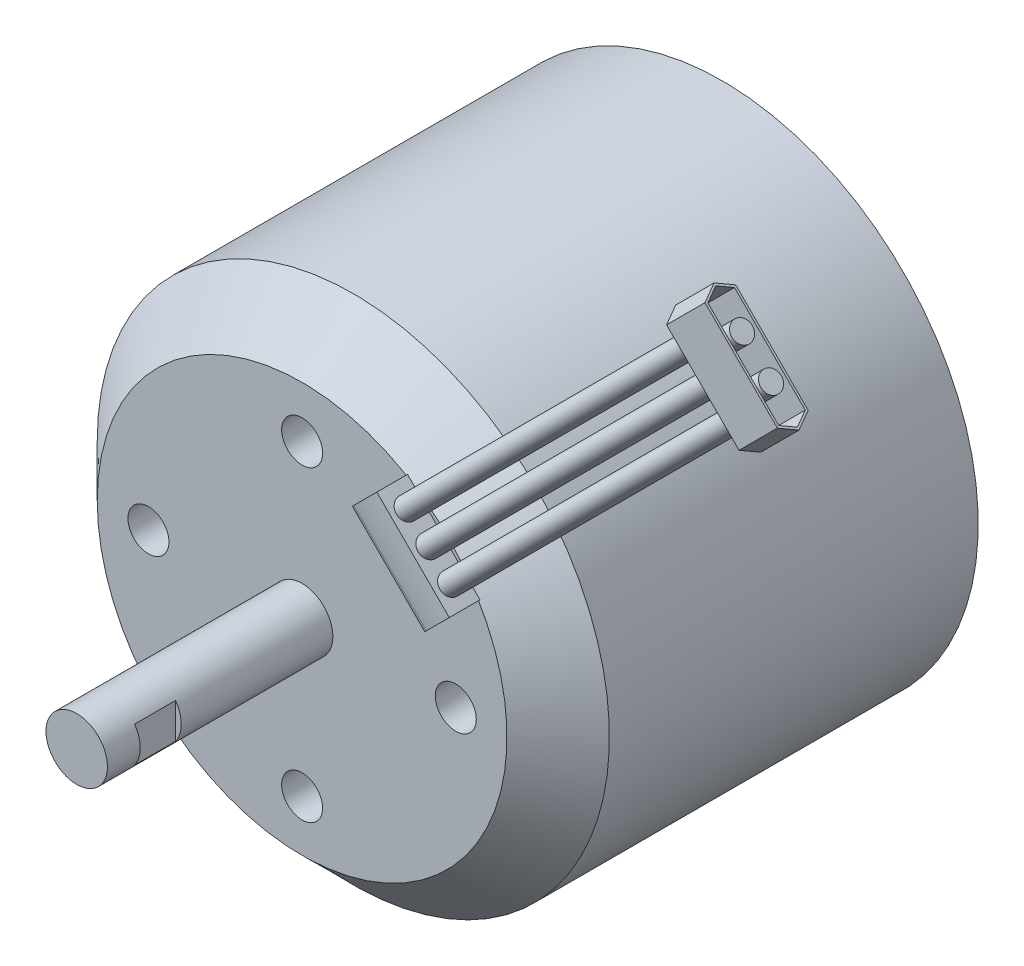
SolidWorks part; units mm, degrees
material "复合材料"
ref_plane "前视基准面" through (0, 0, 0) normal (0, 0, 1) x (1, 0, 0)
ref_plane "上视基准面" through (0, 0, 0) normal (0, 1, 0) x (1, 0, 0)
ref_plane "右视基准面" through (0, 0, 0) normal (1, 0, 0) x (0, 0, -1)
sketch "草图1" plane through (0, 0, 0) normal (1, 0, 0) x (0, 0, -1)
  line L0 (0, 0) -> (-91.143, 0) construction
  line L1 (0, 0) -> (0, 95.1998) construction
  line L2 (-2, 25) -> (-38, 25)
  line L4 (-43, 20) -> (-43, 3)
  line L5 (-43, 3) -> (-65, 3)
  line L6 (-65, 3) -> (-65, 0)
  line L7 (-65, 0) -> (0, 0)
  line L9 (-2, 25) -> (-2, 3)
  line L10 (-2, 3) -> (0, 3)
  line L11 (0, 3) -> (0, 0)
  line L12 (-38, 25) -> (-43, 20)
  dimension "D1" = 65
  dimension "D2" = 22
  dimension "D3" = 6
  dimension "D4" = 41
  dimension "D5" = 6
  dimension "D6" = 50
  dimension "D7" = 5
  dimension "D8" = 135
revolve "旋转1" add sketch "草图1" angle 360 about L0
sketch "草图2" plane through (0, 0, 43) normal (0, 0, 1) x (1, 0, 0)
  circle A0 centre (0, 0) radius 15 construction
  dimension "D1" = 30
sketch "草图3" plane through (0, 0, 2) normal (0, 0, -1) x (-1, 0, 0)
  circle A0 centre (0, 0) radius 10 construction
  dimension "D1" = 20
hole_wizard "M4 螺纹孔1" positions "草图4" profile "草图5" tap size "M4" standard "GB"
sketch "草图4" plane through (0, 0, 43) normal (0, 0, 1) x (1, 0, 0)
  circle A0 centre (0, 0) radius 15 construction
  point P0 (0, 15)
  point P4 (15, 0)
  point P6 (0, -15)
  point P8 (-15, 0)
sketch "草图5" plane through (0, 15, 43) normal (1, 0, 0) x (0, -1, 0)
  line L0 (0, 0) -> (0, 7.3017)
  line L1 (0, 7.3017) -> (2, 6.1)
  line L2 (2, 6.1) -> (2, 0)
  line L5 (2, 0) -> (0, 0)
  line L10 (0, 7.3017) -> (-2, 6.1) construction
  line L11 (0, -6.35) -> (0, 107.95) construction
  dimension "螺纹孔钻头直径" = 4
  dimension "螺纹孔钻头深度" = 6.1
  dimension "导头角度" = 118
cosmetic thread "孔螺蚊线1" parameters "D1"=4, "D2"=4
cosmetic thread "孔螺蚊线2" parameters "D1"=4, "D2"=4
cosmetic thread "孔螺蚊线3" parameters "D1"=4, "D2"=4
cosmetic thread "孔螺蚊线4" parameters "D1"=4, "D2"=4
hole_wizard "M3 螺纹孔1" positions "草图6" profile "草图7" tap size "M3" standard "GB"
sketch "草图6" plane through (0, 0, 2) normal (0, 0, -1) x (-1, 0, 0)
  circle A0 centre (0, 0) radius 10 construction
  point P0 (0, 10)
  point P4 (10, 0)
  point P6 (0, -10)
  point P8 (-10, 0)
sketch "草图7" plane through (0, 10, 2) normal (1, 0, 0) x (0, 1, 0)
  line L0 (0, 0) -> (0, 6.4013)
  line L1 (0, 6.4013) -> (1.5, 5.5)
  line L2 (1.5, 5.5) -> (1.5, 0)
  line L5 (1.5, 0) -> (0, 0)
  line L10 (0, 6.4013) -> (-1.5, 5.5) construction
  line L11 (0, -6.35) -> (0, 107.95) construction
  dimension "螺纹孔钻头直径" = 3
  dimension "螺纹孔钻头深度" = 5.5
  dimension "导头角度" = 118
cosmetic thread "孔螺蚊线5" parameters "D1"=4, "D2"=3
cosmetic thread "孔螺蚊线6" parameters "D1"=4, "D2"=3
cosmetic thread "孔螺蚊线7" parameters "D1"=4, "D2"=3
cosmetic thread "孔螺蚊线8" parameters "D1"=4, "D2"=3
sketch "草图8" plane through (0, 0, 43) normal (0, 0, 1) x (1, 0, 0)
  line L0 (0, 26.4035) -> (0, 0) construction
  line L5 (6.7175, 13.7886) -> (13.7886, 6.7175)
  line L6 (6.7175, 13.7886) -> (8.8388, 15.9099)
  line L7 (8.8388, 15.9099) -> (15.9099, 8.8388)
  line L8 (13.7886, 6.7175) -> (15.9099, 8.8388)
  line L9 (6.7175, 13.7886) -> (15.9099, 8.8388) construction
  line L10 (8.8388, 15.9099) -> (13.7886, 6.7175) construction
  line L11 (0, 0) -> (21.7327, 21.7327) construction
  point P0 (11.3137, 11.3137)
  dimension "D1" = 45
  dimension "D2" = 10
  dimension "D3" = 3
  dimension "D4" = 16
ref_plane "基准面1" through (0, 0, 0) normal (-0.7071, 0.7071, 0) x (0.7071, 0.7071, 0)
sketch "草图9" plane through (0, 0, 0) normal (-0.7071, 0.7071, 0) x (0.7071, 0.7071, 0)
  line L1 (16, -43) -> (16, -40.4916) construction
  line L2 (16, -41.4826) -> (16, -43) construction
  line L3 (21.0176, -45.5321) -> (30.1015, -45.5321) construction
  line L4 (17.316, -44.8794) -> (18, -43) construction
  line L5 (21.0176, -45.5321) -> (18, -43) construction
  line L6 (18.6701, -43) -> (0, -43) construction
  arc A0 (16, -43) -> (17.316, -44.8794) centre (18, -43) ccw
  arc A1 (17.316, -44.8794) -> (21.0176, -45.5321) centre (21.0176, -34.7091) ccw
  dimension "D1" = 2
  dimension "D2" = 70
  dimension "D3" = 70
sweep "扫描1" add profiles "草图8" path "草图9"
sketch "草图11" plane through (14.8617, 14.8617, 0) normal (0.7071, 0.7071, 0) x (0, 0, -1)
  line L0 (-47.0321, 0) -> (-44.0321, 0) construction
  line L1 (-47.0321, 5) -> (-47.0321, -5) construction
  line L2 (-44.0321, -5) -> (-44.0321, 5) construction
  line L3 (-45.5321, -5) -> (-45.5321, 5) construction
  line L4 (-47.0321, -5) -> (-44.0321, -5) construction
  line L5 (-44.0321, 5) -> (-47.0321, 5) construction
  circle A0 centre (-45.5321, 0) radius 1
  circle A1 centre (-45.5321, 3) radius 1
  circle A2 centre (-45.5321, -3) radius 1
  dimension "D1" = 6
  dimension "2" = 2
extrude "凸台-拉伸1" add sketch "草图11" along normal blind 40
sketch "草图12" plane through (43.146, 43.146, 0) normal (0.7071, 0.7071, 0) x (0, 0, -1)
  line L0 (-45.5321, 5) -> (-45.5321, -5) construction
  line L1 (-47.0321, -5) -> (-45.5321, -5.866)
  line L2 (-45.5321, -5.866) -> (-44.0321, -5)
  line L3 (-47.0321, 0) -> (-44.0321, 0) construction
  line L4 (-47.0321, -5) -> (-44.0321, -5)
  line L5 (-44.0321, -5) -> (-44.0321, 5)
  line L6 (-44.0321, 5) -> (-47.0321, 5)
  line L7 (-47.0321, 5) -> (-47.0321, -5)
  line L8 (-47.0321, -5) -> (-44.0321, -5) construction
  line L9 (-44.0321, -5) -> (-44.0321, 5)
  line L10 (-44.0321, 5) -> (-47.0321, 5) construction
  line L11 (-47.0321, 5) -> (-47.0321, -5)
  line L12 (-45.5321, 5.866) -> (-44.0321, 5)
  line L13 (-47.0321, 5) -> (-45.5321, 5.866)
  dimension "D2" = 120
  dimension "D1" = 0
extrude "凸台-拉伸2" add sketch "草图12" along normal blind 0.3
sketch "草图13" plane through (43.3581, 43.3581, 0) normal (0.7071, 0.7071, 0) x (0, 0, -1)
  line L0 (-46.8321, 4.8845) -> (-46.8321, -4.8845)
  line L1 (-46.8321, -4.8845) -> (-45.5321, -5.6351)
  line L2 (-45.5321, -5.6351) -> (-44.2321, -4.8845)
  line L3 (-44.2321, -4.8845) -> (-44.2321, 4.8845)
  line L4 (-44.2321, 4.8845) -> (-45.5321, 5.6351)
  line L5 (-45.5321, 5.6351) -> (-46.8321, 4.8845)
  line L6 (-47.0321, 5) -> (-47.0321, -5)
  line L7 (-47.0321, -5) -> (-45.5321, -5.866)
  line L8 (-45.5321, -5.866) -> (-44.0321, -5)
  line L9 (-44.0321, -5) -> (-44.0321, 5)
  line L10 (-44.0321, 5) -> (-45.5321, 5.866)
  line L11 (-45.5321, 5.866) -> (-47.0321, 5)
  line L12 (-47.0321, 5) -> (-47.0321, -5)
  line L13 (-47.0321, -5) -> (-45.5321, -5.866)
  line L14 (-45.5321, -5.866) -> (-44.0321, -5)
  line L15 (-44.0321, -5) -> (-44.0321, 5)
  line L16 (-44.0321, 5) -> (-45.5321, 5.866)
  line L17 (-45.5321, 5.866) -> (-47.0321, 5)
  line L18 (-47.0321, 0) -> (-44.0321, 0) construction
  line L19 (-45.5321, 5.6351) -> (-45.5321, -5.6351) construction
  circle A0 centre (-45.5321, -2) radius 1
  circle A1 centre (-45.5321, 2) radius 1
  dimension "D3" = 2
  dimension "D4" = 4
  dimension "D1" = 0
  dimension "D2" = 0.2
extrude "凸台-拉伸3" add sketch "草图13" along normal blind 5
ref_plane "基准面2" through (0, 0, 61.8) normal (0, 0, 1) x (1, 0, 0)
sketch "草图14" plane through (0, 0, 61.8) normal (0, 0, 1) x (1, 0, 0)
  line L0 (-2.45, 1.7313) -> (-2.45, -1.7313)
  line L1 (2.45, 1.7313) -> (2.45, -1.7313)
  circle A0 centre (0, 0) radius 3 construction
  arc A1 (-2.45, 1.7313) -> (-2.45, -1.7313) centre (0, 0) ccw
  arc A2 (2.45, -1.7313) -> (2.45, 1.7313) centre (0, 0) ccw
  dimension "D1" = 4.9
extrude "切除-拉伸1" cut sketch "草图14" against normal blind 4
ref_plane "基准面3" through (0, 0, 53) normal (0, 0, 1) x (1, 0, 0)
sketch "草图15" plane through (0, 0, 53) normal (0, 0, 1) x (1, 0, 0)
  line L0 (-2.45, -1.7313) -> (-2.45, 1.7313) construction
  line L1 (-2.45, -1.7313) -> (-2.45, 1.7313)
  arc A0 (-2.45, 1.7313) -> (-2.45, -1.7313) centre (0, 0) ccw construction
  arc A1 (-2.45, 1.7313) -> (-2.45, -1.7313) centre (0, 0) ccw
extrude "切除-拉伸2" cut sketch "草图15" against normal up to surface (10 mm away) up to face at (11.3137, 11.3137, 43)
